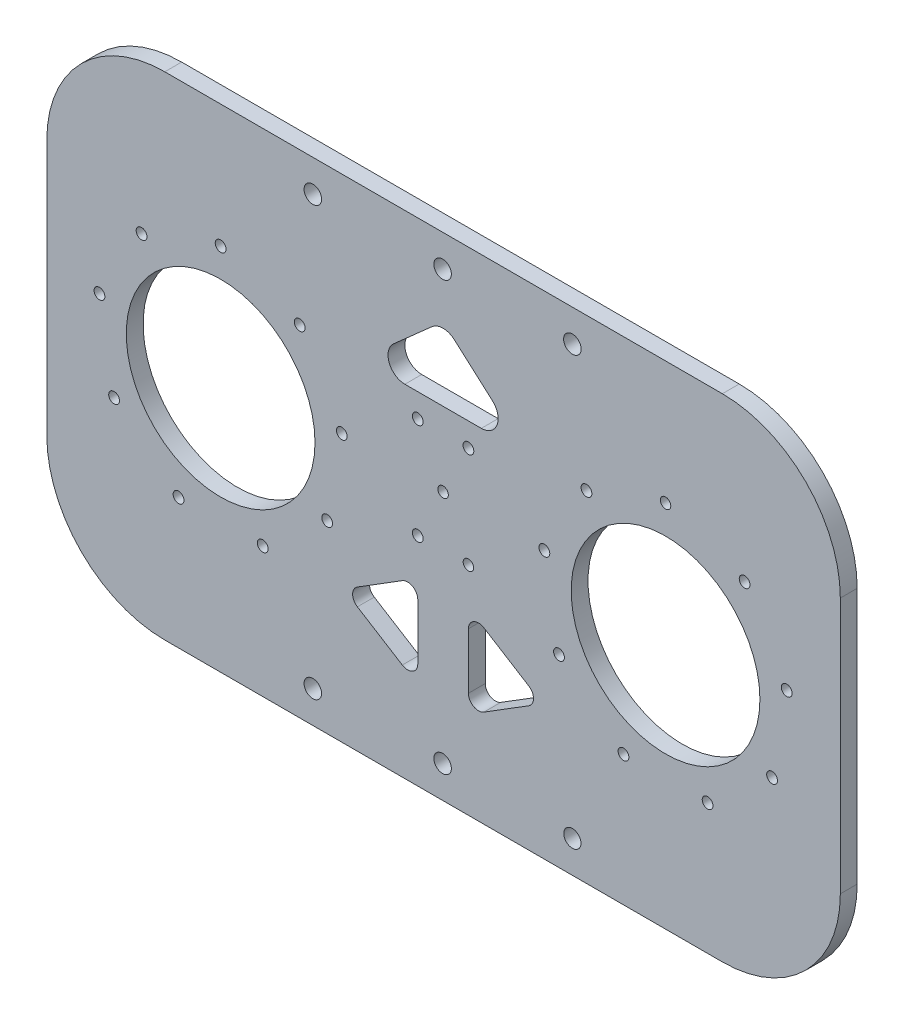
SolidWorks part; units mm, degrees
ref_plane "前视基准面" through (0, 0, 0) normal (0, 0, 1) x (1, 0, 0)
ref_plane "上视基准面" through (0, 0, 0) normal (0, 1, 0) x (1, 0, 0)
ref_plane "右视基准面" through (0, 0, 0) normal (1, 0, 0) x (0, 0, -1)
other "Configuration Table"
sketch "草图1" plane through (0, 0, 0) normal (0, 0, 1) x (1, 0, 0)
  line L0 (-63, 73) -> (47, 73)
  line L2 (-63, 73) -> (-172.4244, 73)
  line L5 (-173, -73) -> (47, -73)
  line L8 (-172.4244, 73) -> (-180.4244, 73)
  line L9 (47, 73) -> (55, 73)
  line L10 (-180.4244, 73) -> (-180.4244, -73)
  line L14 (-180.4244, -73) -> (-173, -73)
  line L15 (55, 73) -> (55, -73)
  line L16 (55, -73) -> (47, -73)
  line L17 (-63, -53.5) -> (-180.4244, -53.5) construction
  line L18 (-101.5, 53.5) -> (-180.4244, 53.5) construction
  line L19 (-180.4244, 53.5) -> (55, 53.5) construction
  line L20 (-62.7122, 53.5) -> (-63, -53.5)
  line L21 (-63, -53.5) -> (55, -53.5) construction
  line L22 (-63, 73) -> (-63, -53.5) construction
  line L23 (-63, -53.5) -> (-62.8561, 0)
  line L24 (-62.8561, 0) -> (-128.8561, 0)
  line L27 (-62.8561, 0) -> (3.1439, 0)
  circle A0 centre (-101.5, 63.5) radius 2.6
  circle A1 centre (-63, 63.5) radius 2.6
  circle A2 centre (-24.5, 63.5) radius 2.6
  circle A3 centre (-24.5, -63.5) radius 2.55
  circle A4 centre (-63, -63.5) radius 2.6
  circle A5 centre (-101.5, -63.5) radius 2.6
  circle A6 centre (-128.8561, 0) radius 40 construction
  circle A7 centre (3.1439, 0) radius 40 construction
  circle A8 centre (-128.8561, 0) radius 36.5 construction
  circle A9 centre (3.1439, 0) radius 36.5 construction
  circle A10 centre (-128.8561, 36.5) radius 1.6
  circle A11 centre (-152.3179, 27.9606) radius 1.6
  circle A12 centre (-164.8016, 6.3382) radius 1.6
  circle A13 centre (-160.466, -18.25) radius 1.6
  circle A14 centre (-141.3398, -34.2988) radius 1.6
  circle A15 centre (-116.3724, -34.2988) radius 1.6
  circle A16 centre (-105.3944, 27.9606) radius 1.6
  circle A17 centre (-92.9106, 6.3382) radius 1.6
  circle A18 centre (-97.2462, -18.25) radius 1.6
  circle A19 centre (3.1439, 36.5) radius 1.55
  circle A20 centre (-20.3179, 27.9606) radius 1.6
  circle A21 centre (-32.8016, 6.3382) radius 1.6
  circle A22 centre (-28.466, -18.25) radius 1.6
  circle A23 centre (-9.3398, -34.2988) radius 1.6
  circle A24 centre (15.6276, -34.2988) radius 1.6
  circle A25 centre (34.7538, -18.25) radius 1.6
  circle A26 centre (39.0894, 6.3382) radius 1.6
  circle A27 centre (26.6056, 27.9606) radius 1.6
  circle A28 centre (-128.8561, 0) radius 28
  circle A29 centre (3.1439, 0) radius 28
  point P21 (-63, 73)
  point P24 (-63, -73)
  point P38 (-128.8561, 36.5)
  point P39 (-152.3179, 27.9606)
  point P40 (-164.8016, 6.3382)
  point P43 (-160.466, -18.25)
  point P44 (-141.3398, -34.2988)
  point P45 (-116.3724, -34.2988)
  point P46 (-97.2462, -18.25)
  point P47 (-92.9106, 6.3382)
  point P48 (-105.3944, 27.9606)
  point P65 (3.1439, 36.5)
  point P66 (26.6056, 27.9606)
  point P69 (39.0894, 6.3382)
  point P70 (34.7538, -18.25)
  point P71 (15.6276, -34.2988)
  point P72 (-9.3398, -34.2988)
  point P73 (-28.466, -18.25)
  point P74 (-32.8016, 6.3382)
  point P75 (-20.3179, 27.9606)
  dimension "D1" = 9
  dimension "D2" = 9
extrude "凸台-拉伸2" add sketch "草图1" along normal blind 5
sketch "草图3" plane through (0, 0, 5) normal (0, 0, 1) x (1, 0, 0)
  line L0 (-180.4244, 73) -> (-180.4244, 38)
  line L1 (-180.4244, 73) -> (-180.4244, -73) construction
  line L2 (-180.4244, 73) -> (-145.4244, 73)
  line L3 (-180.4244, 73) -> (55, 73) construction
  line L4 (-180.4244, -73) -> (-180.4244, -38)
  line L5 (-180.4244, -73) -> (-145.4244, -73)
  line L6 (55, -73) -> (-180.4244, -73) construction
  line L7 (55, 73) -> (20, 73)
  line L8 (55, 73) -> (55, 38)
  line L9 (55, 73) -> (55, -73) construction
  line L10 (55, -38) -> (55, -73)
  line L11 (55, -73) -> (20, -73)
  arc A0 (-180.4244, 38) -> (-145.4244, 73) centre (-145.4244, 38) cw
  arc A1 (-180.4244, -38) -> (-145.4244, -73) centre (-145.4244, -38) ccw
  arc A2 (20, 73) -> (55, 38) centre (20, 38) cw
  arc A3 (20, -73) -> (55, -38) centre (20, -38) ccw
extrude "切除-拉伸1" cut sketch "草图3" against normal blind 10
sketch "草图4" plane through (0, 0, 5) normal (0, 0, 1) x (1, 0, 0)
  circle A0 centre (-70.3697, 21.3382) radius 1.6
  circle A1 centre (-55.3425, 21.3382) radius 1.6
  circle A2 centre (-70.3697, -8.6618) radius 1.6
  circle A3 centre (-55.3425, -8.6618) radius 1.55
extrude "切除-拉伸2" cut sketch "草图4" against normal blind 10
sketch "草图6" plane through (0, 0, 5) normal (0, 0, 1) x (1, 0, 0)
  line L0 (-82.3697, 28.3382) -> (-87.3697, 28.3382)
  line L4 (-43.3425, 28.3382) -> (-38.3425, 28.3382)
  line L5 (-70.3697, -19.6618) -> (-70.3697, -47.0405)
  line L8 (-70.3697, -47.0405) -> (-92.3697, -33.3512)
  line L9 (-55.3425, -19.6618) -> (-55.3425, -47.0405)
  line L10 (-92.3697, -33.3512) -> (-70.3697, -19.6618)
  line L11 (-55.3425, -47.0405) -> (-33.3425, -33.3512)
  line L12 (-33.3425, -33.3512) -> (-55.3425, -19.6618)
  line L14 (-62.8561, 50.0702) -> (-87.3697, 28.3382)
  line L15 (-82.3697, 28.3382) -> (-43.3425, 28.3382)
  line L18 (-38.3425, 28.3382) -> (-62.8561, 50.0702)
  circle A0 centre (-62.8561, 6.3382) radius 1.55
extrude "切除-拉伸3" cut sketch "草图6" against normal blind 10
fillet "圆角4" radius 3 1 edges at (-70.3697, -19.6618, 2.5)
fillet "圆角5" radius 3 1 edges at (-92.3697, -33.3512, 2.5)
fillet "圆角6" radius 3 1 edges at (-70.3697, -47.0405, 2.5)
fillet "圆角7" radius 3 1 edges at (-55.3425, -47.0405, 2.5)
fillet "圆角8" radius 3 1 edges at (-55.3425, -19.6618, 2.5)
fillet "圆角9" radius 3 1 edges at (-33.3425, -33.3512, 2.5)
fillet "圆角10" radius 5 1 edges at (-62.8561, 50.0702, 2.5)
fillet "圆角11" radius 5 1 edges at (-87.3697, 28.3382, 2.5)
fillet "圆角12" radius 5 1 edges at (-38.3425, 28.3382, 2.5)
